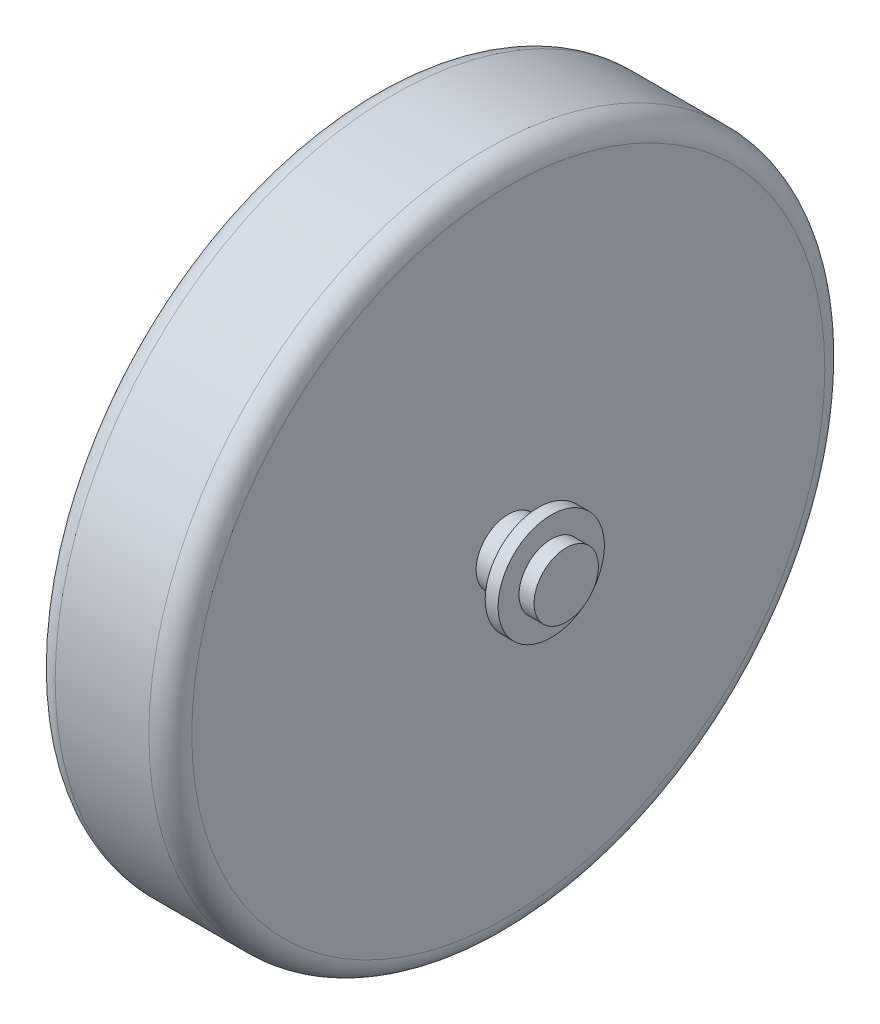
SolidWorks part; units mm, degrees
ref_plane "Front Plane" through (0, 0, 0) normal (0, 0, 1) x (1, 0, 0)
ref_plane "Top Plane" through (0, 0, 0) normal (0, 1, 0) x (1, 0, 0)
ref_plane "Right Plane" through (0, 0, 0) normal (1, 0, 0) x (0, 0, -1)
sketch "Sketch1" plane through (0, 0, 0) normal (0, 1, 0) x (1, 0, 0)
  line L1 (-27, 157.5) -> (-27, 15)
  line L2 (-90.65, 63.5) -> (-90.65, 157.5)
  line L3 (-90.65, 157.5) -> (-27, 157.5)
  line L4 (-27, 15) -> (-13, 15)
  line L5 (-13, 15) -> (-13, 24.7657)
  line L6 (-13, 24.7657) -> (-7, 24.7657)
  line L7 (-7, 24.7657) -> (-7, 15)
  line L8 (-7, 15) -> (0, 15)
  line L9 (0, 15) -> (0, 0)
  line L10 (-90.65, 63.5) -> (-97, 63.5)
  line L11 (-97, 63.5) -> (-97, 47)
  line L12 (-97, 47) -> (-119, 47)
  line L16 (-119, 47) -> (-119, 0)
  line L18 (-119, 0) -> (0, 0)
  dimension "D1" = 63.65
  dimension "D2" = 70
  dimension "D3" = 142.5
  dimension "D4" = 14
  dimension "D5" = 6
  dimension "D6" = 7
  dimension "D7" = 15
  dimension "D8" = 0
  dimension "D11" = 22
revolve "Revolve1" add sketch "Sketch1" angle 360 about L18
fillet "Fillet1" radius 10 2 edges at (-27, 0, 157.5) (-90.65, 0, 157.5)
sketch "Sketch2" plane through (-97, 0, 0) normal (-1, 0, 0) x (0, 0, 1)
  line L0 (0, 0) -> (0, 58) construction
  line L1 (0, 0) -> (50.2295, 29) construction
  circle A0 centre (0, 0) radius 58 construction
  circle A1 centre (0, 58) radius 3.175
  circle A2 centre (50.2295, 29) radius 3.175
  circle A3 centre (50.2295, -29) radius 3.175
  circle A4 centre (0, -58) radius 3.175
  circle A5 centre (-50.2295, -29) radius 3.175
  circle A6 centre (-50.2295, 29) radius 3.175
  dimension "D1" = 116
  dimension "D2" = 6.35
  dimension "D3" = 6
  dimension "D4" = 60
extrude "Cut-Extrude1" cut sketch "Sketch2" against normal blind 10
